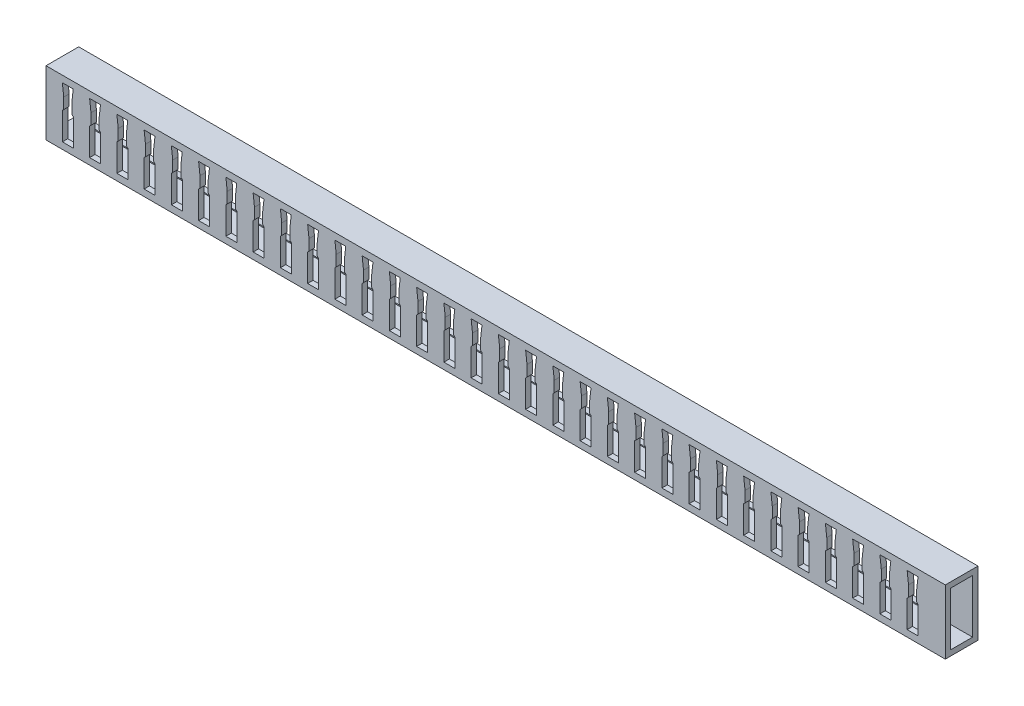
SolidWorks part; units mm, degrees
ref_plane "Front Plane" through (0, 0, 0) normal (0, 0, 1) x (1, 0, 0)
ref_plane "Top Plane" through (0, 0, 0) normal (0, 1, 0) x (1, 0, 0)
ref_plane "Right Plane" through (0, 0, 0) normal (1, 0, 0) x (0, 0, -1)
sketch "Sketch2" plane through (0, 0, 0) normal (1, 0, 0) x (0, 0, -1)
  line L1 (0, 0) -> (15.24, 0)
  line L2 (0, 0) -> (0, 29.972)
  line L3 (0, 29.972) -> (15.24, 29.972)
  line L4 (15.24, 0) -> (15.24, 29.972)
  dimension "D1" = 15.24
  dimension "D2" = 29.972
extrude "Boss-Extrude1" add sketch "Sketch2" along normal blind 419.1
sketch "Sketch3" plane through (419.1, 0, 0) normal (1, 0, 0) x (0, 0, -1)
  line L8 (2.54, 27.432) -> (2.54, 2.54)
  line L9 (2.54, 2.54) -> (12.7, 2.54)
  line L10 (12.7, 2.54) -> (12.7, 27.432)
  line L11 (12.7, 27.432) -> (2.54, 27.432)
  line L12 (2.54, 27.432) -> (2.54, 2.54)
  line L13 (2.54, 2.54) -> (12.7, 2.54)
  line L14 (12.7, 2.54) -> (12.7, 27.432)
  line L15 (12.7, 27.432) -> (2.54, 27.432)
  dimension "D1" = 2.54
extrude "Cut-Extrude1" cut sketch "Sketch3" against normal blind 419.1
sketch "Sketch4" plane through (0, 0, 0) normal (0, 0, 1) x (1, 0, 0)
  line L0 (7.62, 3.048) -> (7.62, 15.748)
  line L1 (7.62, 15.748) -> (8.255, 16.383)
  line L2 (8.255, 16.383) -> (8.255, 21.463)
  line L3 (8.255, 21.463) -> (7.62, 26.924)
  line L4 (7.62, 26.924) -> (12.7, 26.924)
  line L5 (12.7, 26.924) -> (12.065, 21.463)
  line L6 (12.065, 21.463) -> (12.065, 16.383)
  line L7 (12.065, 16.383) -> (12.7, 15.748)
  line L8 (12.7, 15.748) -> (12.7, 3.048)
  line L9 (12.7, 3.048) -> (7.62, 3.048)
  line L10 (419.1, 29.972) -> (0, 29.972) construction
  line L11 (419.1, 0) -> (0, 0) construction
  line L12 (0, 29.972) -> (0, 0) construction
  line L13 (25.4, 3.048) -> (20.32, 3.048)
  line L14 (20.32, 3.048) -> (20.32, 15.748)
  line L15 (20.32, 15.748) -> (20.955, 16.383)
  line L16 (20.955, 16.383) -> (20.955, 21.463)
  line L17 (20.955, 21.463) -> (20.32, 26.924)
  line L18 (20.32, 26.924) -> (25.4, 26.924)
  line L19 (25.4, 26.924) -> (24.765, 21.463)
  line L20 (24.765, 21.463) -> (24.765, 16.383)
  line L21 (24.765, 16.383) -> (25.4, 15.748)
  line L22 (25.4, 15.748) -> (25.4, 3.048)
  line L23 (38.1, 3.048) -> (33.02, 3.048)
  line L24 (33.02, 3.048) -> (33.02, 15.748)
  line L25 (33.02, 15.748) -> (33.655, 16.383)
  line L26 (33.655, 16.383) -> (33.655, 21.463)
  line L27 (33.655, 21.463) -> (33.02, 26.924)
  line L28 (33.02, 26.924) -> (38.1, 26.924)
  line L29 (38.1, 26.924) -> (37.465, 21.463)
  line L30 (37.465, 21.463) -> (37.465, 16.383)
  line L31 (37.465, 16.383) -> (38.1, 15.748)
  line L32 (38.1, 15.748) -> (38.1, 3.048)
  line L33 (50.8, 3.048) -> (45.72, 3.048)
  line L34 (45.72, 3.048) -> (45.72, 15.748)
  line L35 (45.72, 15.748) -> (46.355, 16.383)
  line L36 (46.355, 16.383) -> (46.355, 21.463)
  line L37 (46.355, 21.463) -> (45.72, 26.924)
  line L38 (45.72, 26.924) -> (50.8, 26.924)
  line L39 (50.8, 26.924) -> (50.165, 21.463)
  line L40 (50.165, 21.463) -> (50.165, 16.383)
  line L41 (50.165, 16.383) -> (50.8, 15.748)
  line L42 (50.8, 15.748) -> (50.8, 3.048)
  line L43 (63.5, 3.048) -> (58.42, 3.048)
  line L44 (58.42, 3.048) -> (58.42, 15.748)
  line L45 (58.42, 15.748) -> (59.055, 16.383)
  line L46 (59.055, 16.383) -> (59.055, 21.463)
  line L47 (59.055, 21.463) -> (58.42, 26.924)
  line L48 (58.42, 26.924) -> (63.5, 26.924)
  line L49 (63.5, 26.924) -> (62.865, 21.463)
  line L50 (62.865, 21.463) -> (62.865, 16.383)
  line L51 (62.865, 16.383) -> (63.5, 15.748)
  line L52 (63.5, 15.748) -> (63.5, 3.048)
  line L53 (76.2, 3.048) -> (71.12, 3.048)
  line L54 (71.12, 3.048) -> (71.12, 15.748)
  line L55 (71.12, 15.748) -> (71.755, 16.383)
  line L56 (71.755, 16.383) -> (71.755, 21.463)
  line L57 (71.755, 21.463) -> (71.12, 26.924)
  line L58 (71.12, 26.924) -> (76.2, 26.924)
  line L59 (76.2, 26.924) -> (75.565, 21.463)
  line L60 (75.565, 21.463) -> (75.565, 16.383)
  line L61 (75.565, 16.383) -> (76.2, 15.748)
  line L62 (76.2, 15.748) -> (76.2, 3.048)
  line L63 (88.9, 3.048) -> (83.82, 3.048)
  line L64 (83.82, 3.048) -> (83.82, 15.748)
  line L65 (83.82, 15.748) -> (84.455, 16.383)
  line L66 (84.455, 16.383) -> (84.455, 21.463)
  line L67 (84.455, 21.463) -> (83.82, 26.924)
  line L68 (83.82, 26.924) -> (88.9, 26.924)
  line L69 (88.9, 26.924) -> (88.265, 21.463)
  line L70 (88.265, 21.463) -> (88.265, 16.383)
  line L71 (88.265, 16.383) -> (88.9, 15.748)
  line L72 (88.9, 15.748) -> (88.9, 3.048)
  line L73 (101.6, 3.048) -> (96.52, 3.048)
  line L74 (96.52, 3.048) -> (96.52, 15.748)
  line L75 (96.52, 15.748) -> (97.155, 16.383)
  line L76 (97.155, 16.383) -> (97.155, 21.463)
  line L77 (97.155, 21.463) -> (96.52, 26.924)
  line L78 (96.52, 26.924) -> (101.6, 26.924)
  line L79 (101.6, 26.924) -> (100.965, 21.463)
  line L80 (100.965, 21.463) -> (100.965, 16.383)
  line L81 (100.965, 16.383) -> (101.6, 15.748)
  line L82 (101.6, 15.748) -> (101.6, 3.048)
  line L83 (114.3, 3.048) -> (109.22, 3.048)
  line L84 (109.22, 3.048) -> (109.22, 15.748)
  line L85 (109.22, 15.748) -> (109.855, 16.383)
  line L86 (109.855, 16.383) -> (109.855, 21.463)
  line L87 (109.855, 21.463) -> (109.22, 26.924)
  line L88 (109.22, 26.924) -> (114.3, 26.924)
  line L89 (114.3, 26.924) -> (113.665, 21.463)
  line L90 (113.665, 21.463) -> (113.665, 16.383)
  line L91 (113.665, 16.383) -> (114.3, 15.748)
  line L92 (114.3, 15.748) -> (114.3, 3.048)
  line L93 (127, 3.048) -> (121.92, 3.048)
  line L94 (121.92, 3.048) -> (121.92, 15.748)
  line L95 (121.92, 15.748) -> (122.555, 16.383)
  line L96 (122.555, 16.383) -> (122.555, 21.463)
  line L97 (122.555, 21.463) -> (121.92, 26.924)
  line L98 (121.92, 26.924) -> (127, 26.924)
  line L99 (127, 26.924) -> (126.365, 21.463)
  line L100 (126.365, 21.463) -> (126.365, 16.383)
  line L101 (126.365, 16.383) -> (127, 15.748)
  line L102 (127, 15.748) -> (127, 3.048)
  line L103 (139.7, 3.048) -> (134.62, 3.048)
  line L104 (134.62, 3.048) -> (134.62, 15.748)
  line L105 (134.62, 15.748) -> (135.255, 16.383)
  line L106 (135.255, 16.383) -> (135.255, 21.463)
  line L107 (135.255, 21.463) -> (134.62, 26.924)
  line L108 (134.62, 26.924) -> (139.7, 26.924)
  line L109 (139.7, 26.924) -> (139.065, 21.463)
  line L110 (139.065, 21.463) -> (139.065, 16.383)
  line L111 (139.065, 16.383) -> (139.7, 15.748)
  line L112 (139.7, 15.748) -> (139.7, 3.048)
  line L113 (152.4, 3.048) -> (147.32, 3.048)
  line L114 (147.32, 3.048) -> (147.32, 15.748)
  line L115 (147.32, 15.748) -> (147.955, 16.383)
  line L116 (147.955, 16.383) -> (147.955, 21.463)
  line L117 (147.955, 21.463) -> (147.32, 26.924)
  line L118 (147.32, 26.924) -> (152.4, 26.924)
  line L119 (152.4, 26.924) -> (151.765, 21.463)
  line L120 (151.765, 21.463) -> (151.765, 16.383)
  line L121 (151.765, 16.383) -> (152.4, 15.748)
  line L122 (152.4, 15.748) -> (152.4, 3.048)
  line L123 (165.1, 3.048) -> (160.02, 3.048)
  line L124 (160.02, 3.048) -> (160.02, 15.748)
  line L125 (160.02, 15.748) -> (160.655, 16.383)
  line L126 (160.655, 16.383) -> (160.655, 21.463)
  line L127 (160.655, 21.463) -> (160.02, 26.924)
  line L128 (160.02, 26.924) -> (165.1, 26.924)
  line L129 (165.1, 26.924) -> (164.465, 21.463)
  line L130 (164.465, 21.463) -> (164.465, 16.383)
  line L131 (164.465, 16.383) -> (165.1, 15.748)
  line L132 (165.1, 15.748) -> (165.1, 3.048)
  line L133 (177.8, 3.048) -> (172.72, 3.048)
  line L134 (172.72, 3.048) -> (172.72, 15.748)
  line L135 (172.72, 15.748) -> (173.355, 16.383)
  line L136 (173.355, 16.383) -> (173.355, 21.463)
  line L137 (173.355, 21.463) -> (172.72, 26.924)
  line L138 (172.72, 26.924) -> (177.8, 26.924)
  line L139 (177.8, 26.924) -> (177.165, 21.463)
  line L140 (177.165, 21.463) -> (177.165, 16.383)
  line L141 (177.165, 16.383) -> (177.8, 15.748)
  line L142 (177.8, 15.748) -> (177.8, 3.048)
  line L143 (190.5, 3.048) -> (185.42, 3.048)
  line L144 (185.42, 3.048) -> (185.42, 15.748)
  line L145 (185.42, 15.748) -> (186.055, 16.383)
  line L146 (186.055, 16.383) -> (186.055, 21.463)
  line L147 (186.055, 21.463) -> (185.42, 26.924)
  line L148 (185.42, 26.924) -> (190.5, 26.924)
  line L149 (190.5, 26.924) -> (189.865, 21.463)
  line L150 (189.865, 21.463) -> (189.865, 16.383)
  line L151 (189.865, 16.383) -> (190.5, 15.748)
  line L152 (190.5, 15.748) -> (190.5, 3.048)
  line L153 (203.2, 3.048) -> (198.12, 3.048)
  line L154 (198.12, 3.048) -> (198.12, 15.748)
  line L155 (198.12, 15.748) -> (198.755, 16.383)
  line L156 (198.755, 16.383) -> (198.755, 21.463)
  line L157 (198.755, 21.463) -> (198.12, 26.924)
  line L158 (198.12, 26.924) -> (203.2, 26.924)
  line L159 (203.2, 26.924) -> (202.565, 21.463)
  line L160 (202.565, 21.463) -> (202.565, 16.383)
  line L161 (202.565, 16.383) -> (203.2, 15.748)
  line L162 (203.2, 15.748) -> (203.2, 3.048)
  line L163 (215.9, 3.048) -> (210.82, 3.048)
  line L164 (210.82, 3.048) -> (210.82, 15.748)
  line L165 (210.82, 15.748) -> (211.455, 16.383)
  line L166 (211.455, 16.383) -> (211.455, 21.463)
  line L167 (211.455, 21.463) -> (210.82, 26.924)
  line L168 (210.82, 26.924) -> (215.9, 26.924)
  line L169 (215.9, 26.924) -> (215.265, 21.463)
  line L170 (215.265, 21.463) -> (215.265, 16.383)
  line L171 (215.265, 16.383) -> (215.9, 15.748)
  line L172 (215.9, 15.748) -> (215.9, 3.048)
  line L173 (228.6, 3.048) -> (223.52, 3.048)
  line L174 (223.52, 3.048) -> (223.52, 15.748)
  line L175 (223.52, 15.748) -> (224.155, 16.383)
  line L176 (224.155, 16.383) -> (224.155, 21.463)
  line L177 (224.155, 21.463) -> (223.52, 26.924)
  line L178 (223.52, 26.924) -> (228.6, 26.924)
  line L179 (228.6, 26.924) -> (227.965, 21.463)
  line L180 (227.965, 21.463) -> (227.965, 16.383)
  line L181 (227.965, 16.383) -> (228.6, 15.748)
  line L182 (228.6, 15.748) -> (228.6, 3.048)
  line L183 (241.3, 3.048) -> (236.22, 3.048)
  line L184 (236.22, 3.048) -> (236.22, 15.748)
  line L185 (236.22, 15.748) -> (236.855, 16.383)
  line L186 (236.855, 16.383) -> (236.855, 21.463)
  line L187 (236.855, 21.463) -> (236.22, 26.924)
  line L188 (236.22, 26.924) -> (241.3, 26.924)
  line L189 (241.3, 26.924) -> (240.665, 21.463)
  line L190 (240.665, 21.463) -> (240.665, 16.383)
  line L191 (240.665, 16.383) -> (241.3, 15.748)
  line L192 (241.3, 15.748) -> (241.3, 3.048)
  line L193 (254, 3.048) -> (248.92, 3.048)
  line L194 (248.92, 3.048) -> (248.92, 15.748)
  line L195 (248.92, 15.748) -> (249.555, 16.383)
  line L196 (249.555, 16.383) -> (249.555, 21.463)
  line L197 (249.555, 21.463) -> (248.92, 26.924)
  line L198 (248.92, 26.924) -> (254, 26.924)
  line L199 (254, 26.924) -> (253.365, 21.463)
  line L200 (253.365, 21.463) -> (253.365, 16.383)
  line L201 (253.365, 16.383) -> (254, 15.748)
  line L202 (254, 15.748) -> (254, 3.048)
  line L203 (266.7, 3.048) -> (261.62, 3.048)
  line L204 (261.62, 3.048) -> (261.62, 15.748)
  line L205 (261.62, 15.748) -> (262.255, 16.383)
  line L206 (262.255, 16.383) -> (262.255, 21.463)
  line L207 (262.255, 21.463) -> (261.62, 26.924)
  line L208 (261.62, 26.924) -> (266.7, 26.924)
  line L209 (266.7, 26.924) -> (266.065, 21.463)
  line L210 (266.065, 21.463) -> (266.065, 16.383)
  line L211 (266.065, 16.383) -> (266.7, 15.748)
  line L212 (266.7, 15.748) -> (266.7, 3.048)
  line L213 (279.4, 3.048) -> (274.32, 3.048)
  line L214 (274.32, 3.048) -> (274.32, 15.748)
  line L215 (274.32, 15.748) -> (274.955, 16.383)
  line L216 (274.955, 16.383) -> (274.955, 21.463)
  line L217 (274.955, 21.463) -> (274.32, 26.924)
  line L218 (274.32, 26.924) -> (279.4, 26.924)
  line L219 (279.4, 26.924) -> (278.765, 21.463)
  line L220 (278.765, 21.463) -> (278.765, 16.383)
  line L221 (278.765, 16.383) -> (279.4, 15.748)
  line L222 (279.4, 15.748) -> (279.4, 3.048)
  line L223 (292.1, 3.048) -> (287.02, 3.048)
  line L224 (287.02, 3.048) -> (287.02, 15.748)
  line L225 (287.02, 15.748) -> (287.655, 16.383)
  line L226 (287.655, 16.383) -> (287.655, 21.463)
  line L227 (287.655, 21.463) -> (287.02, 26.924)
  line L228 (287.02, 26.924) -> (292.1, 26.924)
  line L229 (292.1, 26.924) -> (291.465, 21.463)
  line L230 (291.465, 21.463) -> (291.465, 16.383)
  line L231 (291.465, 16.383) -> (292.1, 15.748)
  line L232 (292.1, 15.748) -> (292.1, 3.048)
  line L233 (304.8, 3.048) -> (299.72, 3.048)
  line L234 (299.72, 3.048) -> (299.72, 15.748)
  line L235 (299.72, 15.748) -> (300.355, 16.383)
  line L236 (300.355, 16.383) -> (300.355, 21.463)
  line L237 (300.355, 21.463) -> (299.72, 26.924)
  line L238 (299.72, 26.924) -> (304.8, 26.924)
  line L239 (304.8, 26.924) -> (304.165, 21.463)
  line L240 (304.165, 21.463) -> (304.165, 16.383)
  line L241 (304.165, 16.383) -> (304.8, 15.748)
  line L242 (304.8, 15.748) -> (304.8, 3.048)
  line L243 (317.5, 3.048) -> (312.42, 3.048)
  line L244 (312.42, 3.048) -> (312.42, 15.748)
  line L245 (312.42, 15.748) -> (313.055, 16.383)
  line L246 (313.055, 16.383) -> (313.055, 21.463)
  line L247 (313.055, 21.463) -> (312.42, 26.924)
  line L248 (312.42, 26.924) -> (317.5, 26.924)
  line L249 (317.5, 26.924) -> (316.865, 21.463)
  line L250 (316.865, 21.463) -> (316.865, 16.383)
  line L251 (316.865, 16.383) -> (317.5, 15.748)
  line L252 (317.5, 15.748) -> (317.5, 3.048)
  line L253 (330.2, 3.048) -> (325.12, 3.048)
  line L254 (325.12, 3.048) -> (325.12, 15.748)
  line L255 (325.12, 15.748) -> (325.755, 16.383)
  line L256 (325.755, 16.383) -> (325.755, 21.463)
  line L257 (325.755, 21.463) -> (325.12, 26.924)
  line L258 (325.12, 26.924) -> (330.2, 26.924)
  line L259 (330.2, 26.924) -> (329.565, 21.463)
  line L260 (329.565, 21.463) -> (329.565, 16.383)
  line L261 (329.565, 16.383) -> (330.2, 15.748)
  line L262 (330.2, 15.748) -> (330.2, 3.048)
  line L263 (342.9, 3.048) -> (337.82, 3.048)
  line L264 (337.82, 3.048) -> (337.82, 15.748)
  line L265 (337.82, 15.748) -> (338.455, 16.383)
  line L266 (338.455, 16.383) -> (338.455, 21.463)
  line L267 (338.455, 21.463) -> (337.82, 26.924)
  line L268 (337.82, 26.924) -> (342.9, 26.924)
  line L269 (342.9, 26.924) -> (342.265, 21.463)
  line L270 (342.265, 21.463) -> (342.265, 16.383)
  line L271 (342.265, 16.383) -> (342.9, 15.748)
  line L272 (342.9, 15.748) -> (342.9, 3.048)
  line L273 (355.6, 3.048) -> (350.52, 3.048)
  line L274 (350.52, 3.048) -> (350.52, 15.748)
  line L275 (350.52, 15.748) -> (351.155, 16.383)
  line L276 (351.155, 16.383) -> (351.155, 21.463)
  line L277 (351.155, 21.463) -> (350.52, 26.924)
  line L278 (350.52, 26.924) -> (355.6, 26.924)
  line L279 (355.6, 26.924) -> (354.965, 21.463)
  line L280 (354.965, 21.463) -> (354.965, 16.383)
  line L281 (354.965, 16.383) -> (355.6, 15.748)
  line L282 (355.6, 15.748) -> (355.6, 3.048)
  line L283 (368.3, 3.048) -> (363.22, 3.048)
  line L284 (363.22, 3.048) -> (363.22, 15.748)
  line L285 (363.22, 15.748) -> (363.855, 16.383)
  line L286 (363.855, 16.383) -> (363.855, 21.463)
  line L287 (363.855, 21.463) -> (363.22, 26.924)
  line L288 (363.22, 26.924) -> (368.3, 26.924)
  line L289 (368.3, 26.924) -> (367.665, 21.463)
  line L290 (367.665, 21.463) -> (367.665, 16.383)
  line L291 (367.665, 16.383) -> (368.3, 15.748)
  line L292 (368.3, 15.748) -> (368.3, 3.048)
  line L293 (381, 3.048) -> (375.92, 3.048)
  line L294 (375.92, 3.048) -> (375.92, 15.748)
  line L295 (375.92, 15.748) -> (376.555, 16.383)
  line L296 (376.555, 16.383) -> (376.555, 21.463)
  line L297 (376.555, 21.463) -> (375.92, 26.924)
  line L298 (375.92, 26.924) -> (381, 26.924)
  line L299 (381, 26.924) -> (380.365, 21.463)
  line L300 (380.365, 21.463) -> (380.365, 16.383)
  line L301 (380.365, 16.383) -> (381, 15.748)
  line L302 (381, 15.748) -> (381, 3.048)
  line L303 (393.7, 3.048) -> (388.62, 3.048)
  line L304 (388.62, 3.048) -> (388.62, 15.748)
  line L305 (388.62, 15.748) -> (389.255, 16.383)
  line L306 (389.255, 16.383) -> (389.255, 21.463)
  line L307 (389.255, 21.463) -> (388.62, 26.924)
  line L308 (388.62, 26.924) -> (393.7, 26.924)
  line L309 (393.7, 26.924) -> (393.065, 21.463)
  line L310 (393.065, 21.463) -> (393.065, 16.383)
  line L311 (393.065, 16.383) -> (393.7, 15.748)
  line L312 (393.7, 15.748) -> (393.7, 3.048)
  line L313 (406.4, 3.048) -> (401.32, 3.048)
  line L314 (401.32, 3.048) -> (401.32, 15.748)
  line L315 (401.32, 15.748) -> (401.955, 16.383)
  line L316 (401.955, 16.383) -> (401.955, 21.463)
  line L317 (401.955, 21.463) -> (401.32, 26.924)
  line L318 (401.32, 26.924) -> (406.4, 26.924)
  line L319 (406.4, 26.924) -> (405.765, 21.463)
  line L320 (405.765, 21.463) -> (405.765, 16.383)
  line L321 (405.765, 16.383) -> (406.4, 15.748)
  line L322 (406.4, 15.748) -> (406.4, 3.048)
  dimension "D1" = 3.048
  dimension "D2" = 3.048
  dimension "D3" = 5.08
  dimension "D4" = 3.81
  dimension "D5" = 5.08
  dimension "D6" = 12.7
  dimension "D7" = 5.08
  dimension "D8" = 7.62
  dimension "D10" = 8.89
  dimension "D9" = 32
extrude "Cut-Extrude2" cut sketch "Sketch4" against normal blind 419.1
